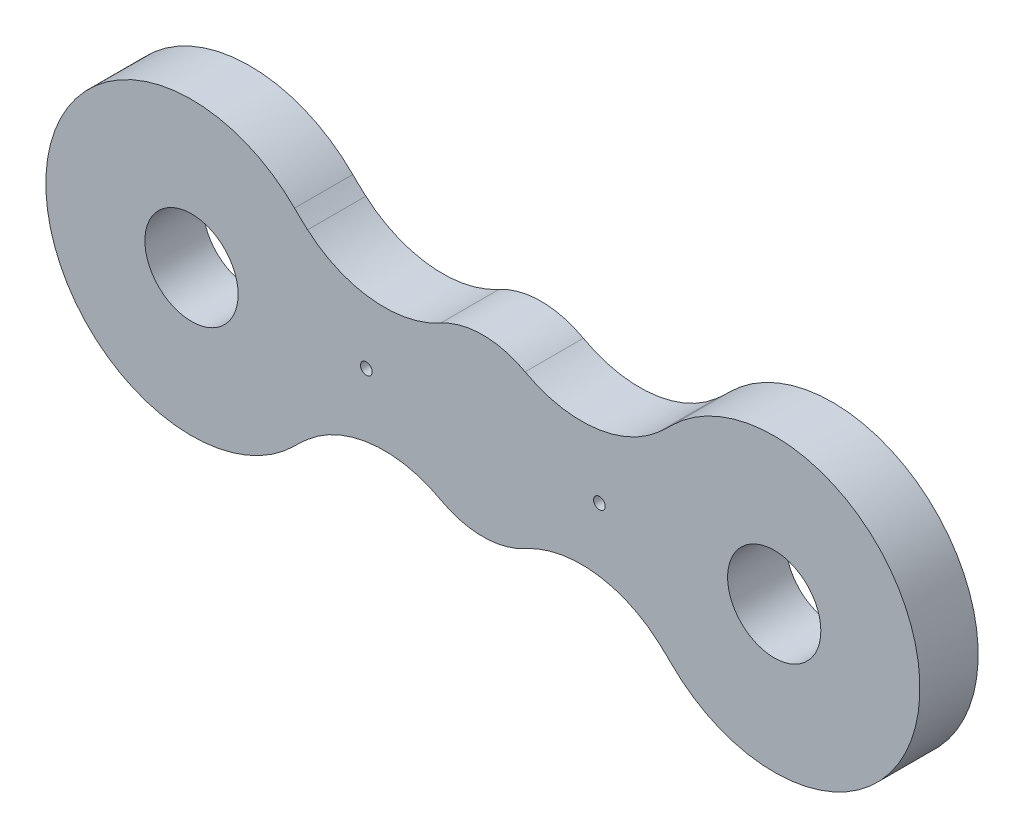
SolidWorks part; units mm, degrees
ref_plane "前基準面" through (0, 0, 0) normal (0, 0, 1) x (1, 0, 0)
ref_plane "上基準面" through (0, 0, 0) normal (0, 1, 0) x (1, 0, 0)
ref_plane "右基準面" through (0, 0, 0) normal (1, 0, 0) x (0, 0, -1)
sketch "草圖1" plane through (0, 0, 0) normal (0, 0, 1) x (1, 0, 0)
  line L0 (-25, 0) -> (25, 0) construction
  line L1 (-25, 0) -> (-16.1612, 8.8388) construction
  line L2 (-16.1612, 8.8388) -> (-16.1612, -8.8388) construction
  line L3 (-16.1612, -8.8388) -> (-25, 0) construction
  line L4 (25, 0) -> (16.1612, 8.8388) construction
  line L5 (16.1612, 8.8388) -> (16.1612, -8.8388) construction
  line L6 (16.1612, -8.8388) -> (25, 0) construction
  circle A0 centre (-25, 0) radius 4
  circle A1 centre (25, 0) radius 4
  arc A2 (-16.1612, 8.8388) -> (-16.1612, -8.8388) centre (-25, 0) ccw
  arc A3 (16.1612, -8.8388) -> (16.1612, 8.8388) centre (25, 0) ccw
  arc A4 (-16.1612, 8.8388) -> (-15.039, 7.7897) centre (0, 25) ccw
  arc A5 (-16.1612, -8.8388) -> (-15.039, -7.7897) centre (0, -25) cw
  arc A6 (-3.6253, -6.5656) -> (3.6253, -6.5656) centre (0, 0) ccw
  arc A7 (3.6253, 6.5656) -> (-3.6253, 6.5656) centre (0, 0) ccw
  arc A8 (15.039, 7.7897) -> (16.1612, 8.8388) centre (0, 25) ccw
  arc A9 (15.039, -7.7897) -> (16.1612, -8.8388) centre (0, -25) cw
  arc A10 (3.6253, -6.5656) -> (15.039, -7.7897) centre (8.4589, -15.3198) cw
  arc A11 (-3.6253, -6.5656) -> (-15.039, -7.7897) centre (-8.4589, -15.3198) ccw
  arc A12 (3.6253, 6.5656) -> (15.039, 7.7897) centre (8.4589, 15.3198) ccw
  arc A13 (-15.039, 7.7897) -> (-3.6253, 6.5656) centre (-8.4589, 15.3198) ccw
  circle A14 centre (-10, 0) radius 0.5
  circle A15 centre (10, 0) radius 0.5
  point P18 (6.7936, -3.1777)
  point P23 (6.7936, 3.1777)
  dimension "D2" = 8
  dimension "D3" = 25
  dimension "D8" = 15
  dimension "D9" = 10
  dimension "D10" = 1
  dimension "D11" = 15
  dimension "D1" = 50
  dimension "D4" = 45
  dimension "D5" = 45
  dimension "D6" = 45
  dimension "D7" = 45
  dimension "D12" = 15
extrude "填料-伸長1" add sketch "草圖1" along normal blind 5
